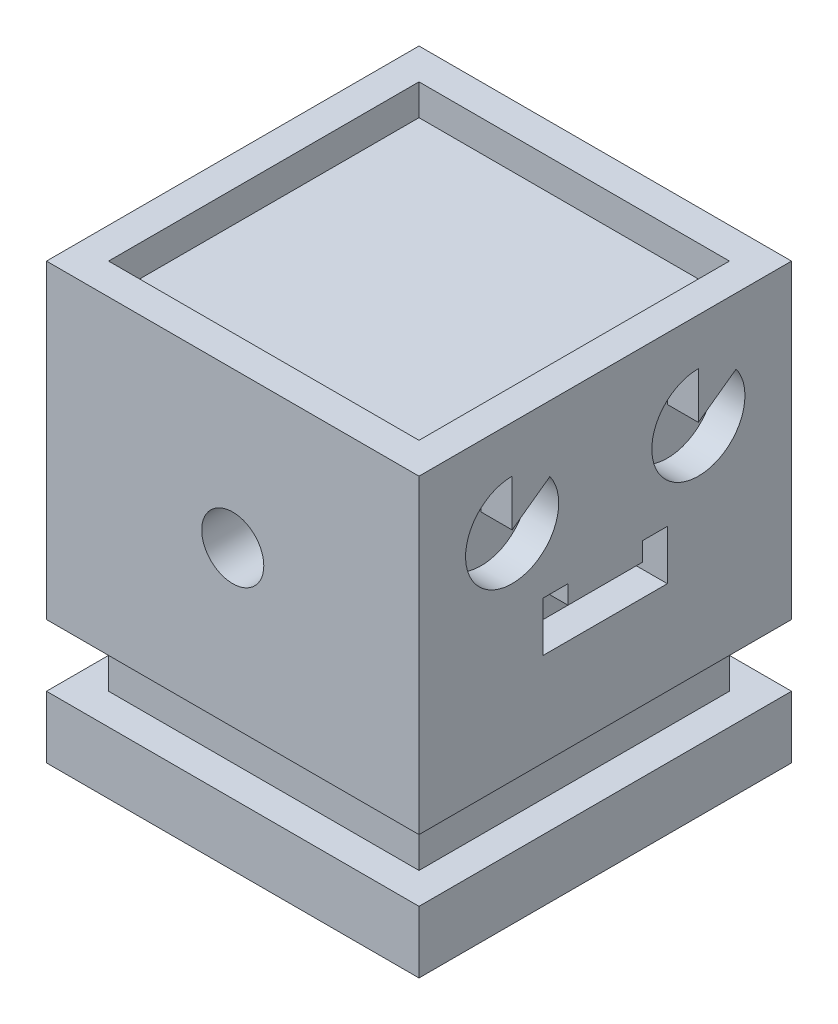
SolidWorks part; units mm, degrees
ref_plane "Front Plane" through (0, 0, 0) normal (0, 0, 1) x (1, 0, 0)
ref_plane "Top Plane" through (0, 0, 0) normal (0, 1, 0) x (1, 0, 0)
ref_plane "Right Plane" through (0, 0, 0) normal (1, 0, 0) x (0, 0, -1)
sketch "Sketch1" plane through (0, 0, 0) normal (0, 0, 1) x (1, 0, 0)
  line L1 (0, 0) -> (60, 0)
  line L2 (0, 0) -> (0, 70)
  line L3 (0, 70) -> (60, 70)
  line L4 (60, 0) -> (60, 70)
  dimension "D1" = 70
  dimension "D2" = 60
extrude "Boss-Extrude3" add sketch "Sketch1" along normal blind 60
sketch "Sketch2" plane through (0, 70, 0) normal (0, 1, 0) x (1, 0, 0)
  line L0 (60, -60) -> (0, -60) construction
  line L1 (5, -55) -> (55, -55)
  line L2 (5, -55) -> (5, -5)
  line L3 (5, -5) -> (55, -5)
  line L4 (55, -55) -> (55, -5)
  line L5 (60, -60) -> (60, 0) construction
  line L6 (60, 0) -> (0, 0) construction
  line L7 (0, -60) -> (0, 0) construction
  dimension "D1" = 5
  dimension "D2" = 5
  dimension "D3" = 5
  dimension "D4" = 5
extrude "Cut-Extrude1" cut sketch "Sketch2" against normal blind 5
sketch "Sketch3" plane through (0, 0, 60) normal (0, 0, 1) x (1, 0, 0)
  line L0 (0, 70) -> (0, 0) construction
  line L1 (0, 10) -> (5, 10)
  line L2 (0, 10) -> (0, 20)
  line L3 (0, 20) -> (5, 20)
  line L4 (60, 10) -> (60, 20)
  line L5 (60, 0) -> (60, 70) construction
  line L6 (60, 70) -> (0, 70) construction
  line L7 (0, 0) -> (60, 0) construction
  line L8 (55, 20) -> (60, 20)
  line L10 (5, 20) -> (5, 10)
  line L12 (55, 20) -> (55, 10)
  line L13 (55, 10) -> (60, 10)
  point P16 (0, 15)
  dimension "D1" = 50
  dimension "D2" = 10
  dimension "D3" = 5
  dimension "D4" = 5
extrude "Cut-Extrude3" cut sketch "Sketch3" against normal through all
sketch "Sketch6" plane through (60, 0, 0) normal (1, 0, 0) x (0, 0, -1)
  line L0 (0, 10) -> (-60, 10) construction
  line L1 (-60, 20) -> (-55, 20)
  line L2 (-60, 20) -> (-60, 10)
  line L3 (-60, 10) -> (-55, 10)
  line L4 (0, 20) -> (0, 10)
  line L5 (0, 20) -> (0, 10) construction
  line L7 (-55, 20) -> (-55, 10)
  line L9 (-5, 20) -> (-5, 10)
  line L10 (-5, 20) -> (0, 20)
  line L11 (-5, 10) -> (0, 10)
  dimension "D1" = 5
  dimension "D2" = 5
  dimension "D3" = 0
extrude "Cut-Extrude4" cut sketch "Sketch6" against normal through all
sketch "Sketch7" plane through (60, 0, 0) normal (1, 0, 0) x (0, 0, -1)
  line L0 (0, 20) -> (0, 70) construction
  line L1 (-36, 40) -> (-24, 40)
  line L2 (-40, 40) -> (-40, 35)
  line L3 (-40, 35) -> (-20, 35)
  line L4 (-20, 40) -> (-20, 35)
  line L6 (-40, 40) -> (-40, 43)
  line L7 (-40, 43) -> (-36, 43)
  line L8 (-36, 40) -> (-36, 43)
  line L10 (-24, 40) -> (-24, 43)
  line L11 (-24, 43) -> (-20, 43)
  line L12 (-20, 40) -> (-20, 43)
  line L13 (-60, 20) -> (-60, 70) construction
  line L14 (0, 20) -> (-60, 20) construction
  point P14 (-36, 41.5)
  dimension "D1" = 20
  dimension "D2" = 20
  dimension "D3" = 12
  dimension "D4" = 4
  dimension "D5" = 3
  dimension "D6" = 5
  dimension "D7" = 15
  dimension "D8" = 8
extrude "Cut-Extrude5" cut sketch "Sketch7" against normal blind 5
sketch "Sketch8" plane through (60, 0, 0) normal (1, 0, 0) x (0, 0, -1)
  line L0 (-60, 20) -> (-60, 70) construction
  line L1 (-60, 70) -> (0, 70) construction
  line L2 (-45, 55) -> (-45, 62.5)
  line L3 (-45, 55) -> (-38.9276, 59.4019)
  line L4 (-15, 55) -> (-8.9276, 59.4019)
  line L5 (-15, 55) -> (-15, 62.5)
  arc A0 (-45, 62.5) -> (-38.9276, 59.4019) centre (-45, 55) ccw
  arc A1 (-15, 62.5) -> (-8.9276, 59.4019) centre (-15, 55) ccw
  dimension "D1" = 15
  dimension "D2" = 15
  dimension "D3" = 15
  dimension "D4" = 6.0724
  dimension "D5" = 2
extrude "Cut-Extrude7" cut sketch "Sketch8" against normal blind 5 contours L2 A0 L3 | L4 A1 L5
sketch "Sketch9" plane through (0, 0, 0) normal (0, -1, 0) x (-1, 0, 0)
  line L0 (0, -60) -> (-60, -60) construction
  line L1 (-50, -50) -> (-10, -50)
  line L2 (-50, -50) -> (-50, -10)
  line L3 (-50, -10) -> (-10, -10)
  line L4 (-10, -50) -> (-10, -10)
  line L5 (-60, -60) -> (-60, 0) construction
  line L6 (0, 0) -> (-60, 0) construction
  line L7 (0, -60) -> (0, 0) construction
  point P8 (-60, -30)
  dimension "D1" = 10
  dimension "D2" = 10
  dimension "D3" = 10
  dimension "D4" = 10
extrude "Cut-Extrude8" cut sketch "Sketch9" against normal blind 60
sketch "Sketch10" plane through (0, 0, 60) normal (0, 0, 1) x (1, 0, 0)
  line L0 (60, 20) -> (60, 70) construction
  line L1 (60, 70) -> (0, 70) construction
  circle A0 centre (30, 45) radius 5
  dimension "D1" = 10
  dimension "D2" = 30
  dimension "D3" = 25
extrude "Cut-Extrude9" cut sketch "Sketch10" against normal through all
